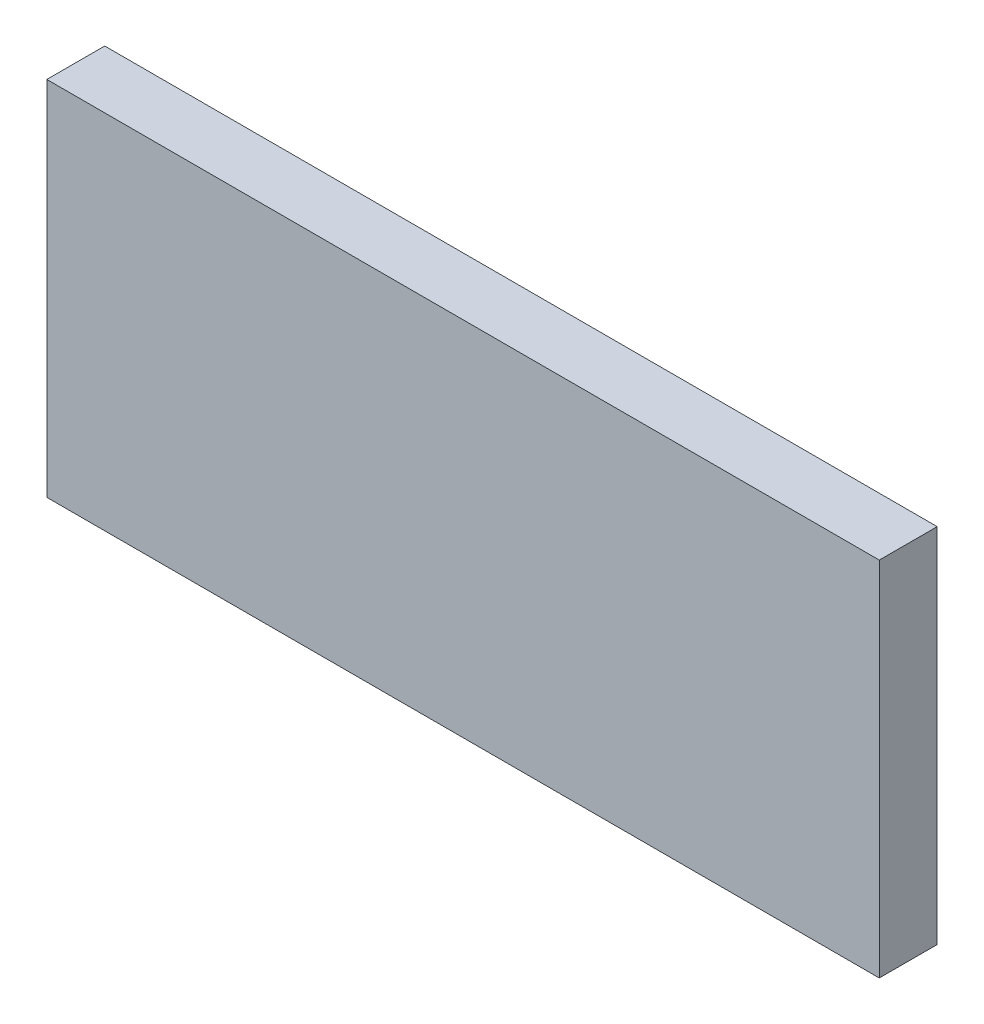
SolidWorks part; units mm, degrees
material "Q235A"
ref_plane "前视" through (0, 0, 0) normal (0, 0, 1) x (1, 0, 0)
ref_plane "上视" through (0, 0, 0) normal (0, 1, 0) x (1, 0, 0)
ref_plane "右视" through (0, 0, 0) normal (1, 0, 0) x (0, 0, -1)
sketch "草图1" plane through (0, 0, 0) normal (0, 0, 1) x (1, 0, 0)
  line L1 (115, -50) -> (-115, -50)
  line L2 (115, -50) -> (115, 50)
  line L3 (115, 50) -> (-115, 50)
  line L4 (-115, -50) -> (-115, 50)
  line L5 (115, -50) -> (-115, 50) construction
  line L6 (115, 50) -> (-115, -50) construction
  point P0 (0, 0)
  dimension "D1" = 100
  dimension "D2" = 230
extrude "凸台-拉伸1" add sketch "草图1" along normal blind 16
hole_wizard "Ø6.0 (6) 直径孔1" positions "草图3" profile "草图2" hole size "Ø6.0" standard "GB"
sketch "草图3" plane through (0, 0, 16) normal (0, 0, 1) x (1, 0, 0)
  point P0 (0, 0)
sketch "草图2" plane through (0, 0, 16) normal (1, 0, 0) x (0, -1, 0)
  line L0 (0, 0) -> (0, 29.0129)
  line L1 (0, 29.0129) -> (15, 20)
  line L2 (15, 20) -> (15, 0)
  line L5 (15, 0) -> (0, 0)
  line L10 (0, 29.0129) -> (-15, 20) construction
  line L11 (0, -6.35) -> (0, 107.95) construction
  dimension "孔直径" = 30
  dimension "孔深度" = 20
  dimension "导头角度" = 118
